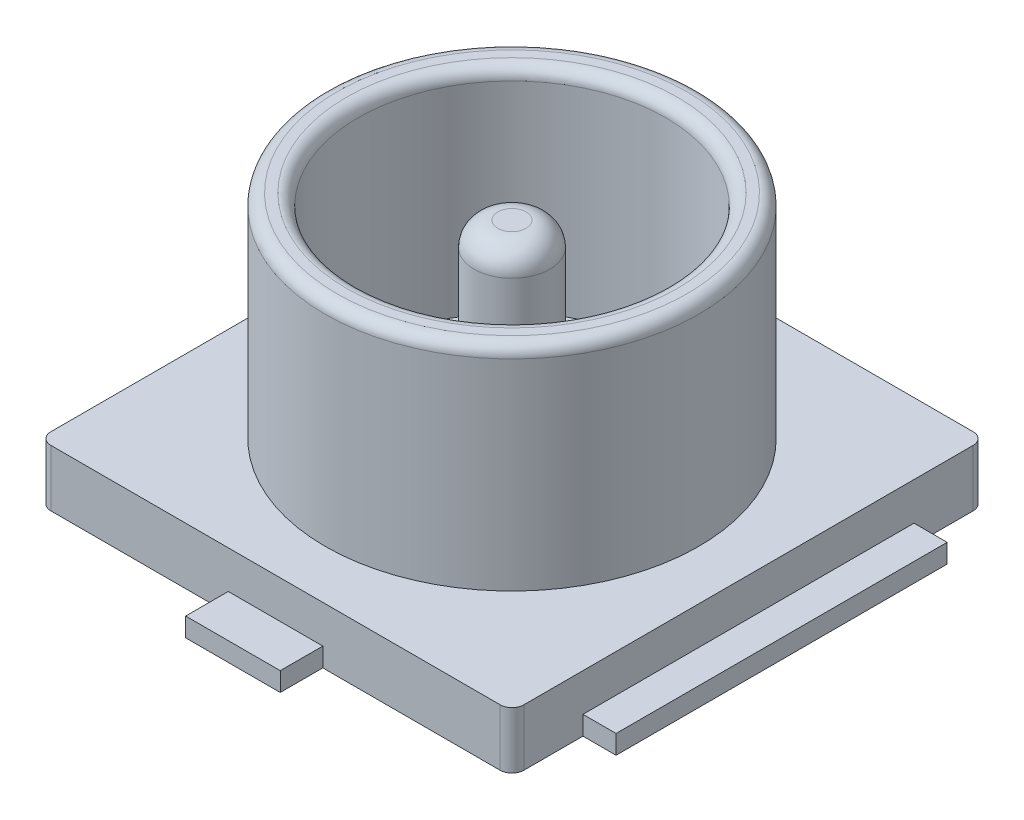
SolidWorks part; units mm, degrees
ref_plane "Front Plane" through (0, 0, 0) normal (0, 0, 1) x (1, 0, 0)
ref_plane "Top Plane" through (0, 0, 0) normal (0, 1, 0) x (1, 0, 0)
ref_plane "Right Plane" through (0, 0, 0) normal (1, 0, 0) x (0, 0, -1)
sketch "Sketch1" plane through (0, 0, 0) normal (0, 1, 0) x (1, 0, 0)
  line L1 (-1.27, 1.27) -> (1.27, 1.27)
  line L2 (-1.27, 1.27) -> (-1.27, -1.27)
  line L3 (-1.27, -1.27) -> (1.27, -1.27)
  line L4 (1.27, 1.27) -> (1.27, -1.27)
  line L5 (-1.27, 1.27) -> (1.27, -1.27) construction
  line L6 (-1.27, -1.27) -> (1.27, 1.27) construction
  point P0 (0, 0)
  dimension "D1" = 2.54
extrude "Boss-Extrude1" add sketch "Sketch1" along normal blind 0.3048
fillet "Fillet2" radius 0.0635 4 edges at (-1.27, 0.1524, -1.27) (1.27, 0.1524, -1.27) (1.27, 0.1524, 1.27) (-1.27, 0.1524, 1.27)
sketch "Sketch2" plane through (0, 0.3048, 0) normal (0, 1, 0) x (1, 0, 0)
  circle A0 centre (0, 0) radius 1.0033
  circle A1 centre (0, 0) radius 0.8255
  dimension "D1" = 2.0066
  dimension "D2" = 1.651
extrude "Boss-Extrude2" add sketch "Sketch2" along normal blind 1.143
fillet "Fillet3" radius 0.0635 2 edges at (0, 1.4478, 0.8255) (0, 1.4478, 1.0033)
sketch "Sketch3" plane through (0, 0.3048, 0) normal (0, 1, 0) x (1, 0, 0)
  circle A0 centre (0, 0) radius 0.2032
  dimension "D1" = 0.4064
extrude "Boss-Extrude3" add sketch "Sketch3" along normal blind 1.016
fillet "Fillet1" radius 0.127 1 edges at (0, 1.3208, 0.2032)
sketch "Sketch4" plane through (0, 0, 0) normal (0, 1, 0) x (1, 0, 0)
  line L0 (-1.2065, -1.27) -> (1.2065, -1.27) construction
  line L1 (-0.254, -1.27) -> (0.254, -1.27)
  line L2 (-0.254, -1.27) -> (-0.254, -1.4986)
  line L3 (-0.254, -1.4986) -> (0.254, -1.4986)
  line L4 (0.254, -1.27) -> (0.254, -1.4986)
  line L5 (1.27, -1.2065) -> (1.27, 1.2065) construction
  line L6 (1.27, -0.889) -> (1.4478, -0.889)
  line L7 (1.27, -0.889) -> (1.27, 0.889)
  line L8 (1.27, 0.889) -> (1.4478, 0.889)
  line L9 (1.4478, -0.889) -> (1.4478, 0.889)
  line L10 (-1.27, 1.2065) -> (-1.27, -1.2065) construction
  line L11 (-1.27, -0.889) -> (-1.4478, -0.889)
  line L12 (-1.27, -0.889) -> (-1.27, 0.889)
  line L13 (-1.27, 0.889) -> (-1.4478, 0.889)
  line L14 (-1.4478, -0.889) -> (-1.4478, 0.889)
  line L15 (-1.27, 1.2065) -> (-1.27, -1.2065) construction
  line L16 (-1.2065, -1.27) -> (1.2065, -1.27) construction
  point P18 (-1.27, 0)
  point P21 (-1.27, 0)
  point P22 (0, -1.27)
  point P25 (0, -1.27)
  dimension "D1" = 0.1778
  dimension "D2" = 1.778
  dimension "D3" = 0.508
  dimension "D4" = 0.2286
extrude "Boss-Extrude4" add sketch "Sketch4" along normal blind 0.1016
